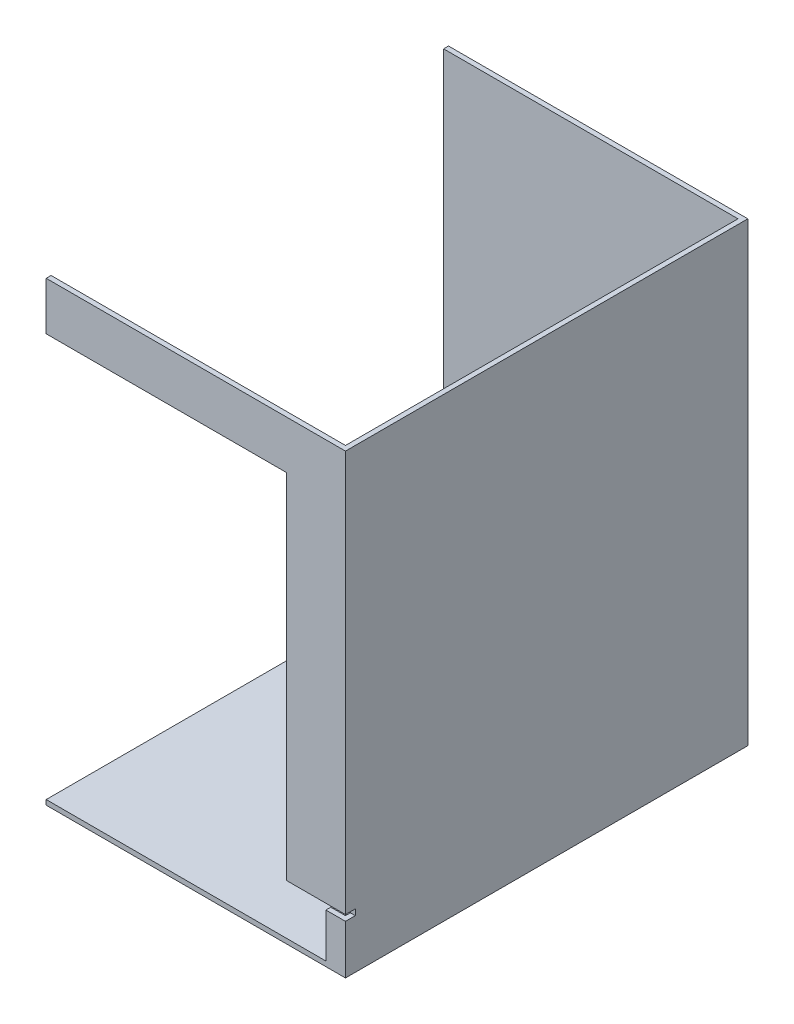
SolidWorks part; units mm, degrees
ref_plane "前视基准面" through (0, 0, 0) normal (0, 0, 1) x (1, 0, 0)
ref_plane "上视基准面" through (0, 0, 0) normal (0, 1, 0) x (1, 0, 0)
ref_plane "右视基准面" through (0, 0, 0) normal (1, 0, 0) x (0, 0, -1)
other "Configuration Table"
sketch "草图8" plane through (0, -2.5, 0) normal (0, -1, 0) x (-1, 0, 0)
  line L1 (-352.1894, -2.2122) -> (-202.1894, -2.2122)
  line L2 (-352.1894, -2.2122) -> (-352.1894, -202.2122)
  line L3 (-352.1894, -202.2122) -> (-202.1894, -202.2122)
  line L4 (-202.1894, -2.2122) -> (-202.1894, -202.2122)
extrude "凸台-拉伸3" add sketch "草图8" against normal blind 230 separate body
shell "抽壳2" thickness 2.5
sketch "草图10" plane through (0, 0, 204.7122) normal (0, 0, 1) x (1, 0, 0)
  line L0 (354.6894, 227.5) -> (354.6894, -5) construction
  line L1 (354.6894, 23) -> (324.6894, 23)
  line L2 (354.6894, 23) -> (354.6894, 20)
  line L3 (354.6894, 20) -> (202.1894, 20)
  line L4 (202.1894, 227.5) -> (202.1894, -5) construction
  line L5 (202.1894, 20) -> (202.1894, 23)
  line L6 (202.1894, 23) -> (202.1894, 203)
  line L7 (202.1894, 203) -> (324.6894, 203)
  line L8 (324.6894, 203) -> (324.6894, 23)
  point P0 (354.6894, 20)
  point P1 (354.6894, 23)
  dimension "D1" = 25
  dimension "D2" = 3
extrude "切除-拉伸3" cut sketch "草图10" against normal blind 5
sketch "草图11" plane through (0, 0, 204.7122) normal (0, 0, 1) x (1, 0, 0)
  line L0 (202.1894, 20) -> (354.6894, 20) construction
  line L1 (344.6894, 20) -> (344.6894, -2.5)
  line L2 (344.6894, -2.5) -> (202.1894, -2.5)
  line L3 (202.1894, -2.5) -> (202.1894, 20)
  line L4 (202.1894, 20) -> (344.6894, 20)
  point P0 (344.6894, 20)
  dimension "D1" = 10
extrude "切除-拉伸4" cut sketch "草图11" against normal blind 5
